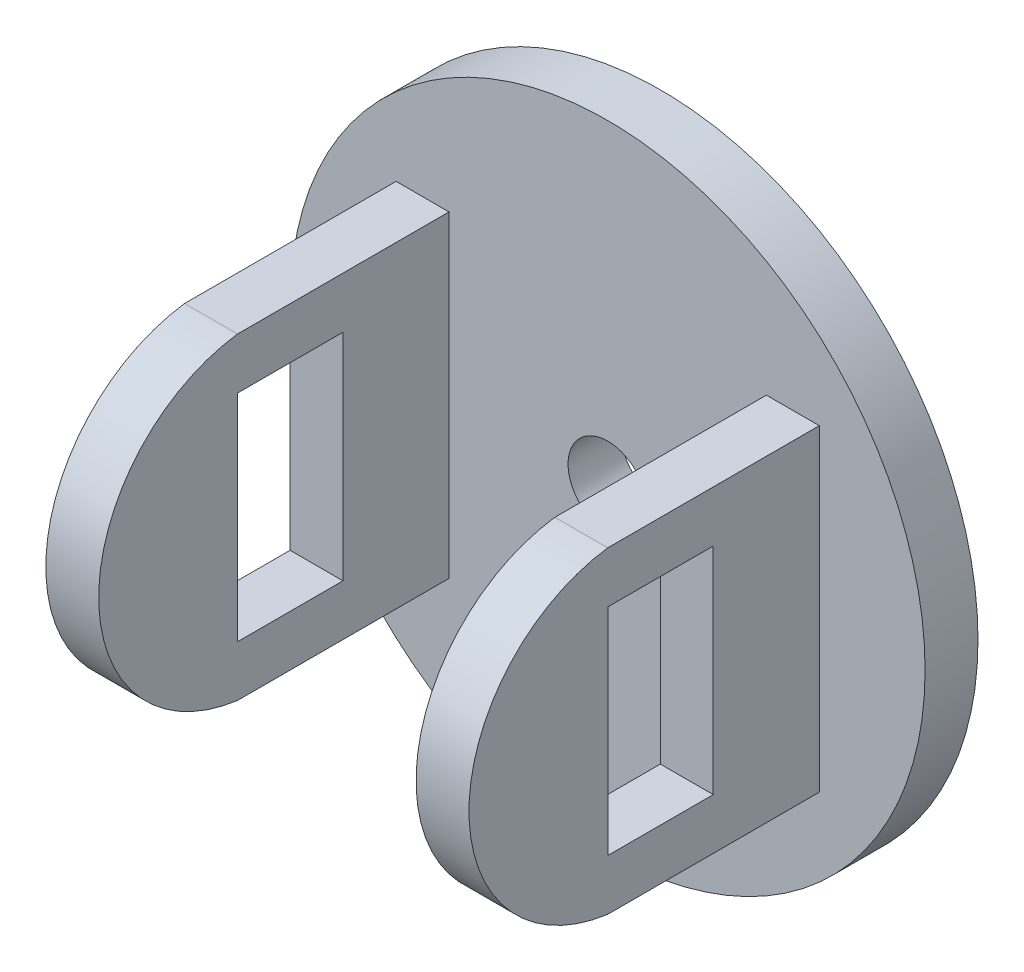
SolidWorks part; units mm, degrees
material "아크릴(내충격성)"
ref_plane "정면" through (0, 0, 0) normal (0, 0, 1) x (1, 0, 0)
ref_plane "윗면" through (0, 0, 0) normal (0, 1, 0) x (1, 0, 0)
ref_plane "우측면" through (0, 0, 0) normal (1, 0, 0) x (0, 0, -1)
sketch "스케치1" plane through (0, 0, 0) normal (0, 0, 1) x (1, 0, 0)
  circle A0 centre (0, 0) radius 60
  dimension "D1" = 120
extrude "보스-돌출1" add sketch "스케치1" along normal blind 10
ref_plane "평면1" through (30, 0, 0) normal (1, 0, 0) x (0, 0, -1)
sketch "스케치3" plane through (30, 0, 0) normal (1, 0, 0) x (0, 0, -1)
  line L1 (-10, 0) -> (-10, 30.0239)
  line L2 (-10, 0) -> (-40, 0) construction
  line L3 (-10, 60) -> (-10, -60) construction
  line L4 (-10, 0) -> (-10, -29.9761)
  line L8 (-10, -29.9761) -> (-50, -29.9761)
  line L9 (-49.95, 20.35) -> (-30.05, 20.35)
  line L10 (-49.95, 20.35) -> (-49.95, -20.35)
  line L11 (-49.95, -20.35) -> (-30.05, -20.35)
  line L12 (-30.05, 20.35) -> (-30.05, -20.35)
  line L13 (-49.95, 20.35) -> (-30.05, -20.35) construction
  line L14 (-49.95, -20.35) -> (-30.05, 20.35) construction
  line L15 (-10, 30.0239) -> (-50, 30.0239)
  arc A3 (-50, -29.9761) -> (-50, 30.0239) centre (-45.953, 0.0239) cw
  dimension "D2" = 40.7
  dimension "D3" = 60
  dimension "D1" = 19.9
ref_plane "평면2" through (-40, 0, 0) normal (1, 0, 0) x (0, 0, -1)
extrude "보스-돌출4" add sketch "스케치3" along normal blind 10
sketch "스케치10" plane through (-40, 0, 0) normal (1, 0, 0) x (0, 0, -1)
  line L0 (-49.95, -20.35) -> (-30.05, -20.35) construction
  line L1 (-30.05, -20.35) -> (-30.05, 20.35) construction
  line L2 (-30.05, 20.35) -> (-49.95, 20.35) construction
  line L3 (-10, 30.0239) -> (-50, 30.0239)
  line L4 (-10, 30.0239) -> (-50, 30.0239)
  line L5 (-10, -29.9761) -> (-10, 30.0239)
  line L8 (-10, -29.9761) -> (-10, 30.0239)
  line L9 (-50, -29.9761) -> (-10, -29.9761)
  line L10 (-50, -29.9761) -> (-10, -29.9761)
  line L11 (-49.95, 20.35) -> (-49.95, -20.35) construction
  line L12 (-49.95, -20.35) -> (-30.05, -20.35)
  line L13 (-30.05, -20.35) -> (-30.05, 20.35)
  line L14 (-30.05, 20.35) -> (-49.95, 20.35)
  line L15 (-49.95, 20.35) -> (-49.95, -20.35)
  arc A1 (-50, 30.0239) -> (-50, -29.9761) centre (-45.953, 0.0239) ccw
  arc A3 (-50, 30.0239) -> (-50, -29.9761) centre (-45.953, 0.0239) ccw
  dimension "D1" = 0
extrude "보스-돌출7" add sketch "스케치10" along normal blind 10
sketch "스케치11" plane through (0, 0, 10) normal (0, 0, 1) x (1, 0, 0)
  circle A0 centre (0, 0) radius 7.5
  dimension "D1" = 15
extrude "컷-돌출1" cut sketch "스케치11" against normal through all
